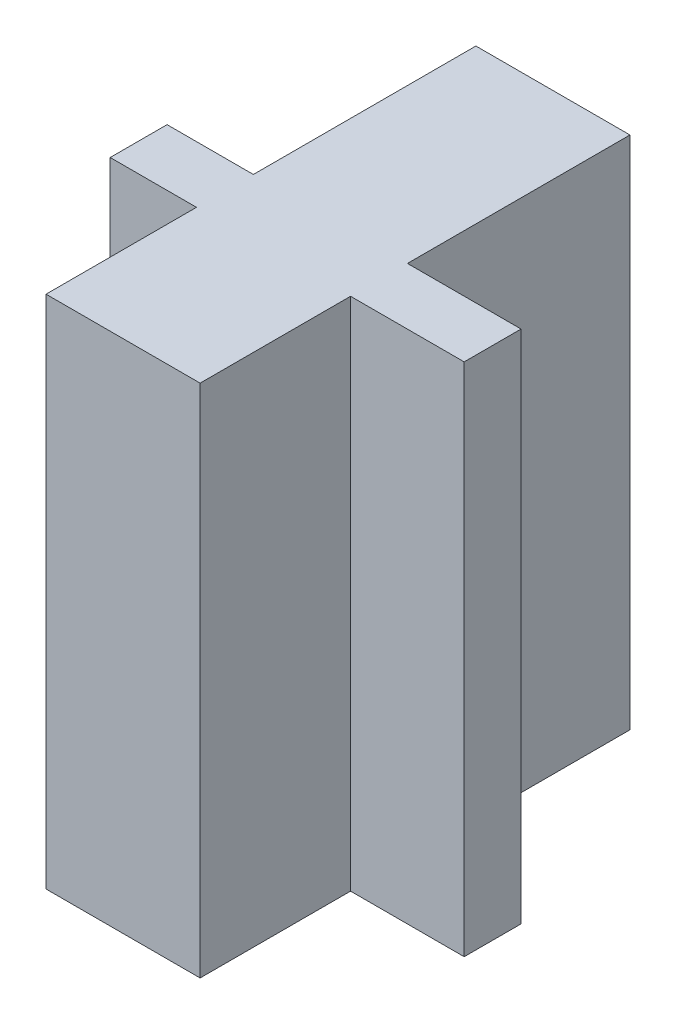
SolidWorks part; units mm, degrees
ref_plane "Front Plane" through (0, 0, 0) normal (0, 0, 1) x (1, 0, 0)
ref_plane "Top Plane" through (0, 0, 0) normal (0, 1, 0) x (1, 0, 0)
ref_plane "Right Plane" through (0, 0, 0) normal (1, 0, 0) x (0, 0, -1)
sketch "Sketch1" plane through (0, 0, 0) normal (0, 1, 0) x (1, 0, 0)
  line L0 (254.6628, 114.3) -> (711.2, 114.3)
  line L1 (-711.2, 114.3) -> (-364.4622, 114.3)
  line L2 (-711.2, 114.3) -> (-711.2, -114.3)
  line L3 (-711.2, -114.3) -> (-364.4622, -114.3)
  line L4 (711.2, 114.3) -> (711.2, -114.3)
  line L5 (-711.2, 114.3) -> (711.2, -114.3) construction
  line L6 (-711.2, -114.3) -> (711.2, 114.3) construction
  line L7 (-364.4622, 1008.3936) -> (254.6628, 1008.3936)
  line L8 (-364.4622, 1008.3936) -> (-364.4622, 114.3)
  line L9 (-364.4622, -718.8064) -> (254.6628, -718.8064)
  line L10 (254.6628, 1008.3936) -> (254.6628, 114.3)
  line L13 (254.6628, -114.3) -> (254.6628, -718.8064)
  line L14 (254.6628, -114.3) -> (711.2, -114.3)
  line L15 (-364.4622, -114.3) -> (-364.4622, -718.8064)
  point P0 (0, 0)
  point P10 (254.6628, -718.8064)
  dimension "D1" = 1422.4
  dimension "D2" = 228.6
  dimension "D3" = 619.125
  dimension "D4" = 1727.2
extrude "Boss-Extrude1" add sketch "Sketch1" along normal blind 2070.1
